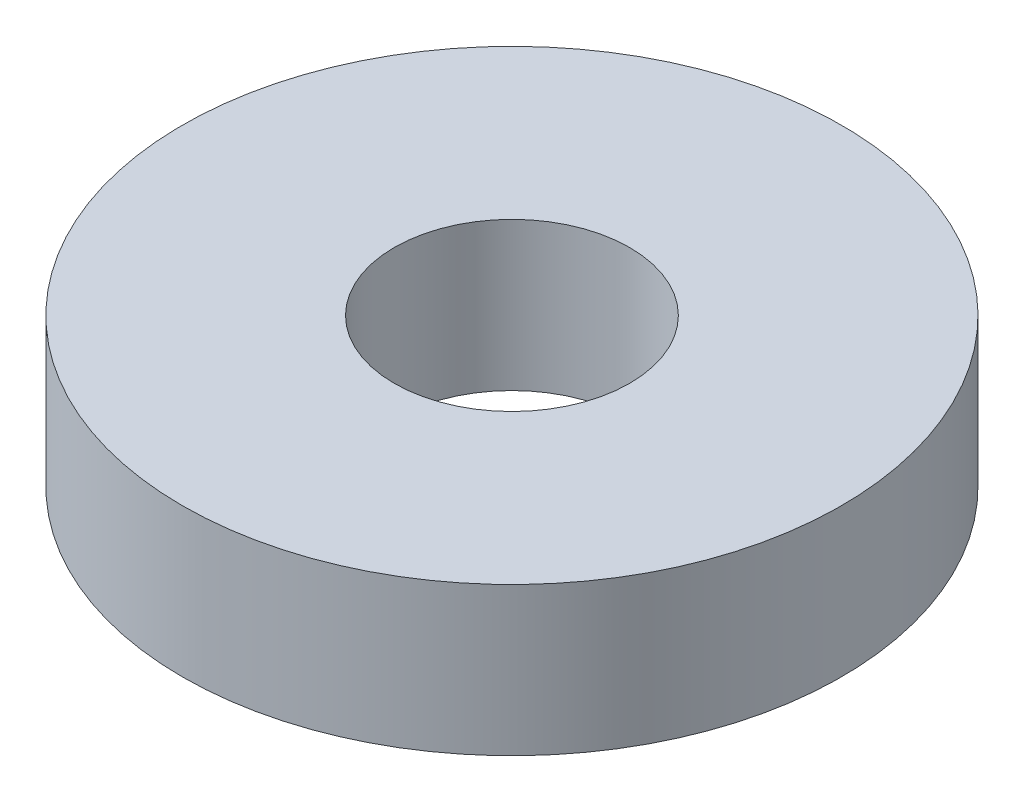
SolidWorks part; units mm, degrees
material "AISI 1020 Steel, Cold Rolled"
ref_plane "Front Plane" through (0, 0, 0) normal (0, 0, 1) x (1, 0, 0)
ref_plane "Top Plane" through (0, 0, 0) normal (0, 1, 0) x (1, 0, 0)
ref_plane "Right Plane" through (0, 0, 0) normal (1, 0, 0) x (0, 0, -1)
sketch "Sketch1" plane through (0, 0, 0) normal (0, 1, 0) x (1, 0, 0)
  circle A0 centre (0, 0) radius 2.3813
  circle A1 centre (0, 0) radius 6.6675
  dimension "D1" = 4.7625
  dimension "D2" = 13.335
extrude "Boss-Extrude1" add sketch "Sketch1" along normal blind 3
